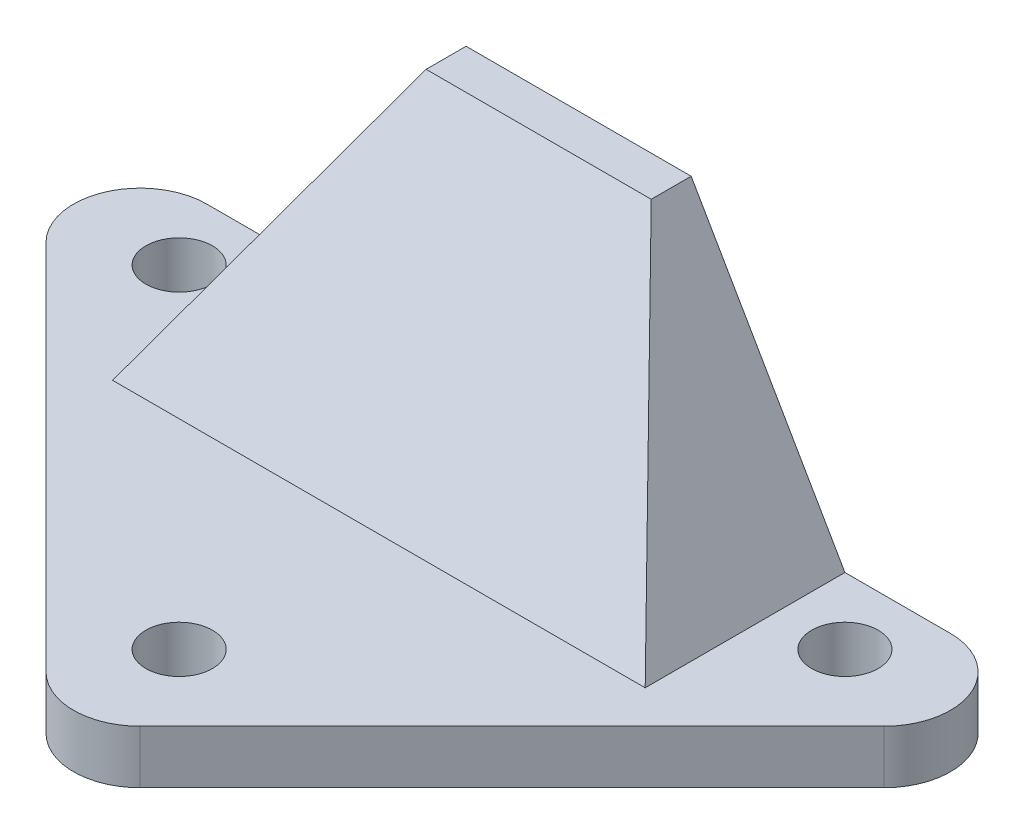
SolidWorks part; units mm, degrees
ref_plane "前视基准面" through (0, 0, 0) normal (0, 0, 1) x (1, 0, 0)
ref_plane "上视基准面" through (0, 0, 0) normal (0, 1, 0) x (1, 0, 0)
ref_plane "右视基准面" through (0, 0, 0) normal (1, 0, 0) x (0, 0, -1)
sketch "草图1" plane through (0, 0, 0) normal (0, 1, 0) x (1, 0, 0)
  line L0 (-27.9289, -4.9473) -> (27.9289, -4.9473)
  line L1 (31.4645, -13.4828) -> (3.5355, -41.4118)
  line L2 (-3.5355, -41.4118) -> (-31.4645, -13.4828)
  circle A0 centre (-25, -9.9473) radius 2.5
  circle A1 centre (25, -9.9473) radius 2.5
  circle A2 centre (0, -34.9473) radius 2.5
  arc A3 (3.5355, -41.4118) -> (-3.5355, -41.4118) centre (0, -37.8762) cw
  arc A4 (-27.9289, -4.9473) -> (-31.4645, -13.4828) centre (-27.9289, -9.9473) ccw
  arc A5 (27.9289, -4.9473) -> (31.4645, -13.4828) centre (27.9289, -9.9473) cw
  point P12 (0, -44.9473)
  point P15 (-40, -4.9473)
  point P18 (40, -4.9473)
  dimension "D3" = 5
  dimension "D4" = 5
  dimension "D7" = 5
  dimension "D9" = 5
  dimension "D10" = 30
  dimension "D12" = 5
  dimension "D2" = 40
  dimension "D5" = 25
  dimension "D6" = 25
  dimension "D8" = 5
  dimension "D11" = 80
extrude "凸台-拉伸1" add sketch "草图1" along normal blind 4
sketch "草图2" plane through (0, 0, 4.9473) normal (0, 0, -1) x (-1, 0, 0)
  line L0 (-20, 4) -> (-8.453, 24)
  line L1 (-27.9289, 4) -> (27.9289, 4) construction
  line L2 (-8.453, 24) -> (8.453, 24)
  line L3 (8.453, 24) -> (20, 4)
  line L4 (20, 4) -> (-20, 4)
  dimension "D1" = 20
  dimension "D2" = 40
  dimension "D3" = 20
  dimension "D4" = 60
  dimension "D5" = 60
extrude "凸台-拉伸2" add sketch "草图2" against normal blind 15
sketch "草图3" plane through (0, 0, 4.9473) normal (0, 0, -1) x (-1, 0, 0)
  line L0 (-27.9289, 0) -> (27.9289, 0) construction
  line L1 (-14, 0) -> (14, 0)
  line L2 (-14, 0) -> (-14, 4)
  line L3 (-14, 4) -> (14, 4)
  line L4 (14, 0) -> (14, 4)
  dimension "D1" = 28
  dimension "D2" = 14
  dimension "D3" = 4
extrude "切除-拉伸1" cut sketch "草图3" against normal blind 8
sketch "草图4" plane through (0, 0, 0) normal (1, 0, 0) x (0, 0, -1)
  line L0 (-19.9473, 24) -> (-7.9473, 24)
  line L2 (-7.9473, 24) -> (-19.9473, 4)
  line L3 (-19.9473, 4) -> (-19.9473, 24)
  dimension "D1" = 12
extrude "切除-拉伸2" cut sketch "草图4" against normal through all both and the other way through all
